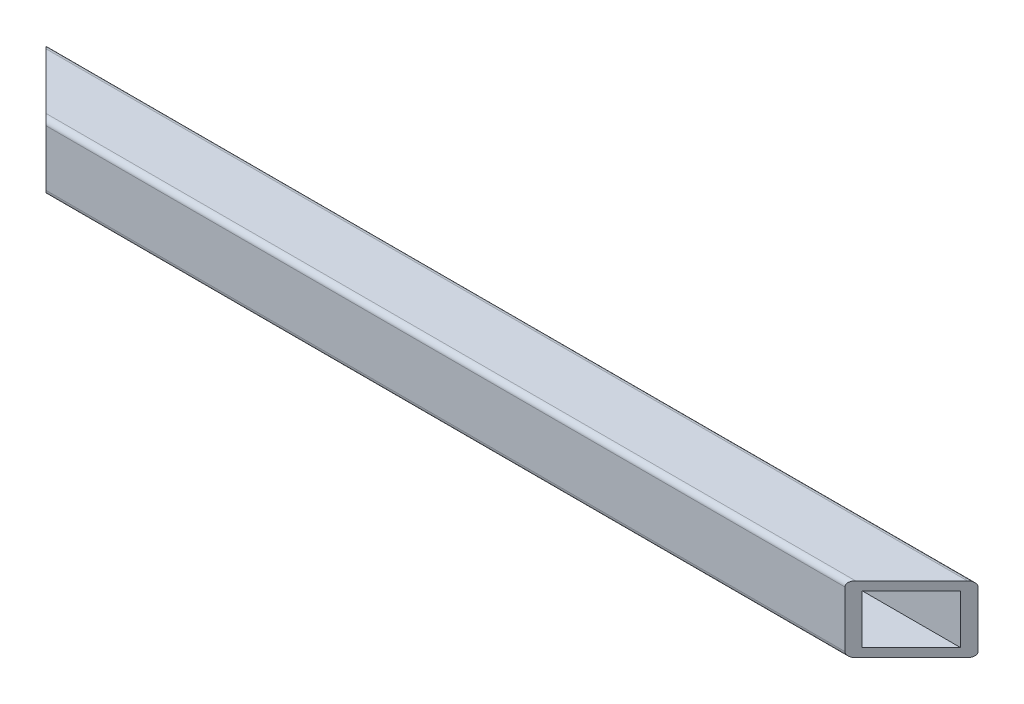
SolidWorks part; units mm, degrees
material "Plain Carbon Steel"
ref_plane "Front Plane" through (0, 0, 0) normal (0, 0, 1) x (1, 0, 0)
ref_plane "Top Plane" through (0, 0, 0) normal (0, 1, 0) x (1, 0, 0)
ref_plane "Right Plane" through (0, 0, 0) normal (1, 0, 0) x (0, 0, -1)
sketch "Sketch1" plane through (0, 0, 0) normal (1, 0, 0) x (0, 0, -1)
  line L0 (0, 2.54) -> (0, 29.21)
  line L1 (-2.54, 31.75) -> (-29.21, 31.75)
  line L2 (-31.75, 29.21) -> (-31.75, 2.54)
  line L3 (-29.21, 0) -> (-2.54, 0)
  line L4 (-4.1275, 4.1275) -> (-4.1275, 27.6225)
  line L5 (-4.1275, 27.6225) -> (-27.6225, 27.6225)
  line L6 (-27.6225, 27.6225) -> (-27.6225, 4.1275)
  line L7 (-27.6225, 4.1275) -> (-4.1275, 4.1275)
  arc A0 (-31.75, 2.54) -> (-29.21, 0) centre (-29.21, 2.54) ccw
  arc A1 (0, 2.54) -> (-2.54, 0) centre (-2.54, 2.54) cw
  arc A2 (0, 29.21) -> (-2.54, 31.75) centre (-2.54, 29.21) ccw
  arc A3 (-31.75, 29.21) -> (-29.21, 31.75) centre (-29.21, 29.21) cw
  arc A4 (-4.1275, 27.6225) -> (-4.1275, 27.6225) centre (-4.1275, 27.6225) ccw
  arc A5 (-27.6225, 27.6225) -> (-27.6225, 27.6225) centre (-27.6225, 27.6225) cw
  arc A6 (-27.6225, 4.1275) -> (-27.6225, 4.1275) centre (-27.6225, 4.1275) ccw
  arc A7 (-4.1275, 4.1275) -> (-4.1275, 4.1275) centre (-4.1275, 4.1275) cw
  point P12 (0, 0)
  point P15 (0, 31.75)
  point P18 (-31.75, 31.75)
  dimension "D3" = 2.54
  dimension "D1" = 31.75
  dimension "D2" = 31.75
  dimension "D4" = 4.1275
extrude "Boss-Extrude1" add sketch "Sketch1" along normal blind 177.8
scale "Scale1" scale about centroid uniform scaling no x scale factor 1 y scale factor 0.4 z scale factor 0.4
sketch "Sketch3" plane through (0, 22.225, 0) normal (0, 1, 0) x (1, 0, 0)
  line L0 (0, -9.525) -> (0, -22.225)
  line L1 (0, -9.525) -> (0, -10.541) construction
  line L2 (177.8, -9.525) -> (0, -9.525) construction
  line L3 (0, -22.225) -> (12.7, -22.225)
  line L4 (177.8, -22.225) -> (0, -22.225) construction
  line L5 (12.7, -22.225) -> (0, -9.525)
  line L6 (88.9, -9.525) -> (88.9, -22.225) construction
  line L7 (177.8, -22.225) -> (165.1, -22.225)
  line L8 (177.8, -9.525) -> (177.8, -22.225)
  line L9 (165.1, -22.225) -> (177.8, -9.525)
extrude "Cut-Extrude3" cut sketch "Sketch3" against normal up to next
